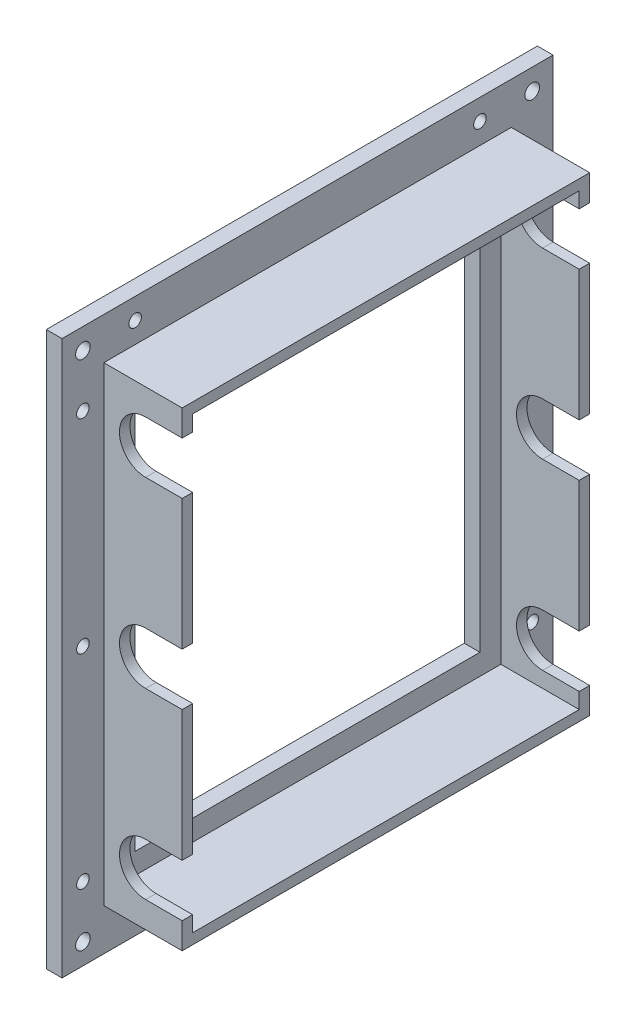
SolidWorks part; units mm, degrees
ref_plane "前视基准面" through (0, 0, 0) normal (0, 0, 1) x (1, 0, 0)
ref_plane "上视基准面" through (0, 0, 0) normal (0, 1, 0) x (1, 0, 0)
ref_plane "右视基准面" through (0, 0, 0) normal (1, 0, 0) x (0, 0, -1)
other "Configuration Table"
sketch "草图1" plane through (0, 0, 0) normal (1, 0, 0) x (0, 0, -1)
  line L0 (-235, 0) -> (0, 0) construction
  line L1 (-235, 265) -> (235, 265)
  line L2 (-235, 265) -> (-235, -265)
  line L3 (-235, -265) -> (235, -265)
  line L4 (235, 265) -> (235, -265)
  line L5 (-235, 265) -> (235, -265) construction
  line L6 (-235, -265) -> (235, 265) construction
  line L7 (-165, 195) -> (165, 195)
  line L8 (-165, 195) -> (-165, -195)
  line L9 (-165, -195) -> (165, -195)
  line L10 (165, 195) -> (165, -195)
  line L11 (-165, 195) -> (165, -195) construction
  line L12 (-165, -195) -> (165, 195) construction
  line L13 (0, 0) -> (0, 265) construction
  circle A0 centre (-215, 245) radius 7
  circle A1 centre (-165, 245) radius 6
  circle A2 centre (-215, 195) radius 6
  circle A3 centre (215, 245) radius 7
  circle A4 centre (165, 245) radius 6
  circle A5 centre (215, 195) radius 6
  circle A6 centre (-215, -195) radius 6
  circle A7 centre (-165, -245) radius 6
  circle A8 centre (-215, -245) radius 7
  circle A9 centre (165, -245) radius 6
  circle A10 centre (215, -245) radius 7
  circle A11 centre (215, -195) radius 6
  circle A12 centre (-215, 0) radius 6
  circle A13 centre (215, 0) radius 6
  point P0 (0, 0)
  point P6 (0, 0)
  dimension "D6" = 490
  dimension "D7" = 14
  dimension "D10" = 12
  dimension "D11" = 12
  dimension "D1" = 390
  dimension "D2" = 330
  dimension "D3" = 470
  dimension "D4" = 530
  dimension "D5" = 430
  dimension "D8" = 330
  dimension "D9" = 390
extrude "凸台-拉伸1" add sketch "草图1" along normal blind 15
sketch "草图2" plane through (15, 0, 0) normal (1, 0, 0) x (0, 0, -1)
  line L0 (-185, 215) -> (185, 215)
  line L1 (-195, 225) -> (195, 225)
  line L2 (-195, 225) -> (-195, -225)
  line L3 (-195, -225) -> (195, -225)
  line L4 (195, 225) -> (195, -225)
  line L5 (-195, 225) -> (195, -225) construction
  line L6 (-195, -225) -> (195, 225) construction
  line L7 (185, 215) -> (185, -215)
  line L8 (-185, -215) -> (185, -215)
  line L9 (-185, 215) -> (-185, -215)
  point P0 (0, 0)
  dimension "D1" = 390
  dimension "D2" = 450
  dimension "D3" = 10
extrude "凸台-拉伸2" add sketch "草图2" along normal blind 75
sketch "草图4" plane through (0, 0, 195) normal (0, 0, 1) x (1, 0, 0)
  line L0 (0, 0) -> (90, 0) construction
  line L1 (90, 225) -> (90, -225) construction
  line L2 (90, 25) -> (55, 25)
  line L3 (55, -25) -> (90, -25)
  line L4 (90, -25) -> (90, 25)
  line L5 (90, 200) -> (55, 200)
  line L6 (55, 150) -> (90, 150)
  line L7 (90, 150) -> (90, 200)
  line L8 (90, -150) -> (90, -200)
  line L9 (55, -150) -> (90, -150)
  line L10 (90, -200) -> (55, -200)
  arc A0 (55, 25) -> (55, -25) centre (55, 0) ccw
  arc A1 (55, 200) -> (55, 150) centre (55, 175) ccw
  arc A2 (55, -200) -> (55, -150) centre (55, -175) cw
  point P16 (90, 175)
  dimension "D1" = 25
  dimension "D2" = 35
  dimension "D3" = 350
  dimension "D4" = 35
extrude "切除-拉伸1" cut sketch "草图4" against normal through all
